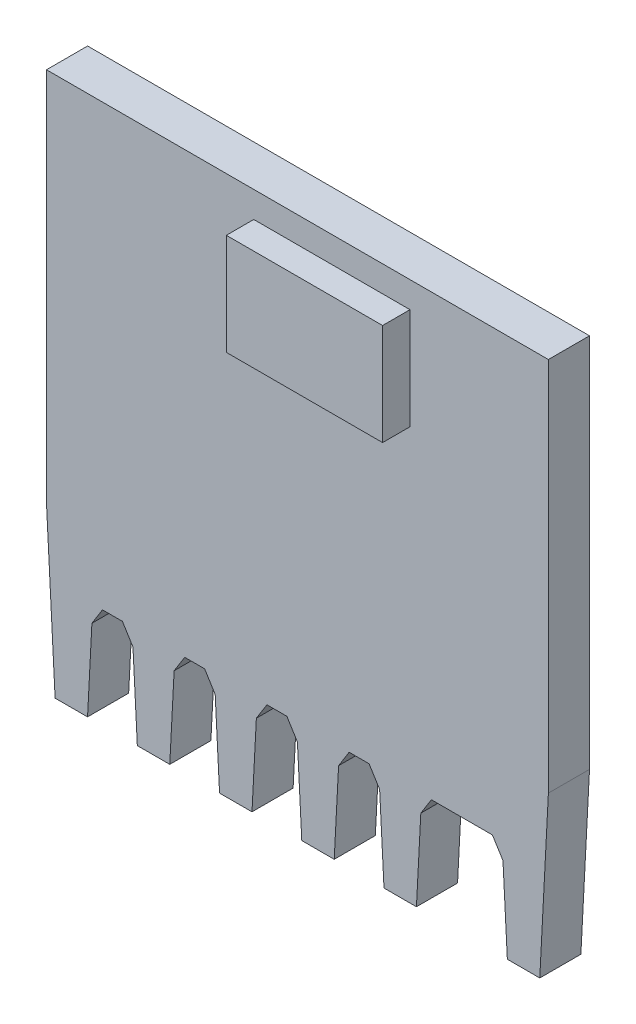
SolidWorks part; units mm, degrees
ref_plane "Front Plane" through (0, 0, 0) normal (0, 0, 1) x (1, 0, 0)
ref_plane "Top Plane" through (0, 0, 0) normal (0, 1, 0) x (1, 0, 0)
ref_plane "Right Plane" through (0, 0, 0) normal (1, 0, 0) x (0, 0, -1)
sketch "Sketch1" plane through (0, 0, 0) normal (0, 0, 1) x (1, 0, 0)
  line L0 (0, 0) -> (0, 19.7) construction
  line L1 (0, 19.7) -> (18.3124, 19.7) construction
  line L2 (18.3124, 19.7) -> (18.3124, 0) construction
  line L3 (18.3124, 0) -> (0, 0) construction
  line L4 (0, 3) -> (18.3124, 3) construction
  line L5 (0, 6) -> (18.3124, 6) construction
  line L6 (0.9062, 6) -> (0.9062, 0) construction
  line L7 (3.9062, 6) -> (3.9062, 0) construction
  line L8 (6.9062, 6) -> (6.9062, 0) construction
  line L9 (9.9062, 6) -> (9.9062, 0) construction
  line L10 (12.9062, 6) -> (12.9062, 0) construction
  line L11 (17.4062, 6) -> (17.4062, 0) construction
  line L12 (0.9062, 3) -> (3.9062, 3) construction
  line L13 (3.9062, 3) -> (6.9062, 3) construction
  line L14 (6.9062, 3) -> (9.9062, 3) construction
  line L15 (9.9062, 3) -> (12.9062, 3) construction
  line L16 (12.9062, 3) -> (17.4062, 3) construction
  line L17 (0.9062, 3) -> (0, 3) construction
  line L18 (17.4062, 3) -> (18.3124, 3) construction
  line L19 (2.4062, 3) -> (2.4062, 0) construction
  line L20 (5.4062, 3) -> (5.4062, 0) construction
  line L21 (8.4062, 3) -> (8.4062, 0) construction
  line L22 (11.4062, 3) -> (11.4062, 0) construction
  line L23 (15.1562, 3) -> (15.1562, 0) construction
  line L24 (14.4062, 3.75) -> (15.9062, 3.75) construction
  line L25 (0, 6) -> (0.3144, 0)
  line L26 (0.3144, 0) -> (1.4979, 0)
  line L27 (1.4979, 0) -> (1.6572, 3.0393)
  line L28 (3.1552, 3.0393) -> (3.3144, 0)
  line L29 (3.3144, 0) -> (4.4979, 0)
  line L30 (4.4979, 0) -> (4.6572, 3.0393)
  line L31 (6.1552, 3.0393) -> (6.3144, 0)
  line L32 (6.3144, 0) -> (7.4979, 0)
  line L33 (7.4979, 0) -> (7.6572, 3.0393)
  line L34 (9.1552, 3.0393) -> (9.3144, 0)
  line L35 (9.3144, 0) -> (10.4979, 0)
  line L36 (10.4979, 0) -> (10.6572, 3.0393)
  line L37 (12.1552, 3.0393) -> (12.3144, 0)
  line L38 (12.3144, 0) -> (13.4979, 0)
  line L39 (13.4979, 0) -> (13.6572, 3.0393)
  line L40 (16.6552, 3.0393) -> (16.8144, 0)
  line L41 (16.8144, 0) -> (17.9979, 0)
  line L42 (17.9979, 0) -> (18.3124, 6)
  line L44 (1.6572, 3.0393) -> (2.0426, 3.656)
  line L45 (0, 6) -> (0, 19.7)
  line L46 (0, 19.7) -> (18.3124, 19.7)
  line L47 (18.3124, 19.7) -> (18.3124, 6)
  line L48 (9.1562, 19.7) -> (9.1562, 6) construction
  line L49 (2.0426, 3.656) -> (2.7698, 3.656)
  line L50 (2.7698, 3.656) -> (3.1552, 3.0393)
  line L51 (4.6572, 3.0393) -> (5.0426, 3.656)
  line L52 (5.0426, 3.656) -> (5.7698, 3.656)
  line L53 (5.7698, 3.656) -> (6.1552, 3.0393)
  line L54 (7.6572, 3.0393) -> (8.0426, 3.656)
  line L55 (8.0426, 3.656) -> (8.7698, 3.656)
  line L56 (8.7698, 3.656) -> (9.1552, 3.0393)
  line L57 (10.6572, 3.0393) -> (11.0426, 3.656)
  line L58 (11.0426, 3.656) -> (11.7698, 3.656)
  line L59 (11.7698, 3.656) -> (12.1552, 3.0393)
  line L60 (13.6572, 3.0393) -> (14.0426, 3.656)
  line L61 (14.0426, 3.656) -> (16.2698, 3.656)
  line L62 (16.2698, 3.656) -> (16.6552, 3.0393)
  arc A0 (3.1552, 3.0393) -> (1.6572, 3.0393) centre (2.4062, 3) ccw construction
  arc A1 (6.1552, 3.0393) -> (4.6572, 3.0393) centre (5.4062, 3) ccw construction
  arc A2 (9.1552, 3.0393) -> (7.6572, 3.0393) centre (8.4062, 3) ccw construction
  arc A3 (12.1552, 3.0393) -> (10.6572, 3.0393) centre (11.4062, 3) ccw construction
  arc A4 (13.6572, 3.0393) -> (14.4062, 3.75) centre (14.4062, 3) cw construction
  arc A5 (16.6552, 3.0393) -> (15.9062, 3.75) centre (15.9062, 3) ccw construction
  dimension "D7" = 0.75
  dimension "D1" = 3
  dimension "D2" = 6
  dimension "D3" = 13.7
  dimension "D4" = 3
  dimension "D6" = 4.5
  dimension "D8" = 3
  dimension "D9" = 18.3124
  dimension "D10" = 19.7
extrude "Boss-Extrude1" add sketch "Sketch1" along normal blind 1.5
sketch "Sketch3" plane through (0, 0, 0) normal (0, 0, 1) x (1, 0, 0)
  line L0 (-0.4005, 6) -> (18.7129, 6)
  line L1 (18.7129, 3) -> (-0.4005, 3) construction
  line L2 (-0.4005, 0) -> (18.7129, 0) construction
  line L3 (-0.4005, -0.5) -> (18.7129, -0.5) construction
  line L4 (18.7129, -0.5) -> (18.7129, 6) construction
  line L5 (-0.4005, 6) -> (-0.4005, -0.5) construction
  line L6 (18.3124, 0) -> (0, 0) construction
  line L7 (0, 3) -> (18.3124, 3) construction
  line L8 (0, 6) -> (18.3124, 6) construction
  line L9 (0.3407, -0.5) -> (0, 6) construction
  line L10 (18.3124, 6) -> (17.9717, -0.5) construction
  line L11 (17.9979, 0) -> (18.3124, 6) construction
  line L12 (0, 6) -> (0.3144, 0) construction
  line L13 (5.4062, 6) -> (5.4062, -0.5) construction
  line L14 (3.9062, 6) -> (3.9062, -0.5) construction
  line L15 (5.4062, 3) -> (5.4062, 0) construction
  line L16 (3.1572, 3) -> (3.3407, -0.5) construction
  line L17 (2.7567, 3) -> (2.9401, -0.5)
  line L18 (3.1552, 3.0393) -> (3.3144, 0) construction
  line L19 (2.9401, -0.5) -> (4.8723, -0.5)
  line L20 (4.8723, -0.5) -> (5.0557, 3)
  line L21 (2.8484, 1.25) -> (3.2478, 1.2709) construction
  line L22 (5.9401, -0.5) -> (5.7567, 3)
  line L26 (7.8723, -0.5) -> (5.9401, -0.5)
  line L27 (8.0557, 3) -> (7.8723, -0.5)
  line L30 (2.4062, -0.5) -> (2.4062, 6) construction
  line L31 (2.4062, 3) -> (2.4062, 0) construction
  line L32 (8.4062, 6) -> (8.4062, -0.5) construction
  line L34 (11.4062, -0.5) -> (11.4062, 6) construction
  line L35 (15.1562, -0.5) -> (15.1562, 6) construction
  line L36 (8.4062, 3) -> (8.4062, 0) construction
  line L37 (11.4062, 3) -> (11.4062, 0) construction
  line L38 (15.1562, 3) -> (15.1562, 0) construction
  line L39 (10.8723, -0.5) -> (11.0557, 3)
  line L40 (8.9401, -0.5) -> (10.8723, -0.5)
  line L41 (8.7567, 3) -> (8.9401, -0.5)
  line L42 (11.9401, -0.5) -> (11.7567, 3)
  line L43 (13.8723, -0.5) -> (11.9401, -0.5)
  line L44 (14.0557, 3) -> (13.8723, -0.5)
  line L45 (16.4401, -0.5) -> (18.3723, -0.5)
  line L46 (16.2567, 3) -> (16.4401, -0.5)
  line L47 (18.3723, -0.5) -> (18.7129, 6)
  line L48 (1.8723, -0.5) -> (-0.0599, -0.5)
  line L49 (2.0557, 3) -> (1.8723, -0.5)
  line L50 (-0.0599, -0.5) -> (-0.4005, 6)
  line L51 (16.2567, 3) -> (14.0557, 3)
  line L52 (11.7567, 3) -> (11.0557, 3)
  line L53 (8.7567, 3) -> (8.0557, 3)
  line L54 (5.7567, 3) -> (5.0557, 3)
  line L55 (2.7567, 3) -> (2.0557, 3)
  dimension "D1" = 0.5
  dimension "D2" = 0.4
ref_plane "Plane1" through (3.9062, 0, 0) normal (1, 0, 0) x (0, 0, -1)
sketch "Sketch4" plane through (3.9062, 0, 0) normal (1, 0, 0) x (0, 0, -1)
  line L0 (0, 6) -> (0, -0.5) construction
  line L1 (0.6, 6) -> (-2.1, 6) construction
  line L2 (0.6, 6) -> (0.6, -0.5) construction
  line L3 (0.6, -0.5) -> (-2.1, -0.5) construction
  line L4 (-2.1, 6) -> (-2.1, -0.5) construction
  line L5 (-0.75, -0.5) -> (-0.75, 6) construction
  line L6 (-1.5, 6) -> (-1.5, -0.5) construction
  line L7 (0.6, 2.4005) -> (-2.1, 2.4005) construction
  line L8 (0.3, 6) -> (0.3, -0.5) construction
  line L9 (0.6, 2.4005) -> (3.846, 6) construction
  line L10 (2.2302, 6) -> (0.6, 4.1923) construction
  line L11 (0.6, 4.1923) -> (1.7139, 3.1878) construction
  line L12 (1.7139, 3.1878) -> (4.25, 6)
  line L13 (4.25, 6) -> (0.6, 6) construction
  line L14 (0.3, 1) -> (-1.8, 1) construction
  line L15 (-2.1, 0) -> (0.6, 0) construction
  line L16 (1.7139, 3.1878) -> (1.4912, 3.3887)
  line L17 (1.4912, 3.3887) -> (0.6, 2.4005)
  line L18 (-3.2139, 3.1878) -> (-5.75, 6)
  line L19 (-3.2139, 3.1878) -> (-2.9912, 3.3887)
  line L20 (-2.9912, 3.3887) -> (-2.1, 2.4005)
  line L21 (-2.1, 6) -> (-5.75, 6) construction
  line L22 (0.6, 3.0724) -> (3.2401, 6) construction
  arc A0 (0.4965, 2.2224) -> (0.6, -0.5) centre (4.2, 1) ccw
  arc A1 (0.6, 2.4005) -> (0.4965, 2.2224) centre (0.9713, 2.0656) ccw
  arc A2 (-2.1, 2.4005) -> (-1.9965, 2.2224) centre (-2.4713, 2.0656) cw
  arc A3 (-1.9965, 2.2224) -> (-2.1, -0.5) centre (-5.7, 1) cw
  dimension "D6" = 0.5
  dimension "D1" = 0.6
  dimension "D2" = 0.3
  dimension "D3" = 1.5
  dimension "D4" = 1
  dimension "D5" = 0.3
  dimension "D7" = 10
sketch "Sketch5" plane through (0, 0, 0) normal (1, 0, 0) x (0, 0, -1)
  line L0 (2.2302, 6) -> (0.6, 4.1923) construction
  line L1 (0.6, 4.1923) -> (1.7139, 3.1878) construction
  line L2 (1.7139, 3.1878) -> (4.25, 6) construction
  line L3 (2.2302, 6) -> (0.6, 4.1923) construction
  line L4 (0.6, 4.1923) -> (1.7139, 3.1878) construction
  line L5 (1.7139, 3.1878) -> (4.25, 6) construction
ref_plane "Plane2" through (0, 2.6105, -2.3541) normal (0, 0.7426, -0.6697) x (1, 0, 0)
sketch "Sketch6" plane through (0, 2.6105, -2.3541) normal (0, 0.7426, -0.6697) x (1, 0, 0)
  line L1 (3.9062, -2.362) -> (3.9062, -0.862) construction
  line L2 (3.9062, -2.362) -> (3.9062, -5.0612) construction
  line L3 (4.6562, -5.0612) -> (3.1562, -5.0612)
  line L4 (4.6562, -1.612) -> (3.1562, -1.612) construction
  line L5 (3.1562, -1.612) -> (3.1562, -5.0612)
  line L6 (4.6562, -1.612) -> (4.6562, -5.0612)
  line L10 (2.4062, -5.0612) -> (15.1562, -5.0612) construction
  line L11 (15.1562, -5.0612) -> (15.1562, -0.862) construction
  line L12 (15.1562, -0.862) -> (2.4062, -0.862) construction
  line L13 (2.4062, -0.862) -> (2.4062, -5.0612) construction
  line L14 (15.1562, 0.3349) -> (15.1562, -4.0182) construction
  line L15 (2.4062, 0.3349) -> (2.4062, -4.0182) construction
  line L16 (11.4062, -5.0612) -> (11.4062, -0.862) construction
  line L17 (8.4062, -5.0612) -> (8.4062, -0.862) construction
  line L18 (5.4062, -5.0612) -> (5.4062, -0.862) construction
  line L19 (5.4062, -4.0182) -> (5.4062, 0.3349) construction
  line L20 (8.4062, -4.0182) -> (8.4062, 0.3349) construction
  line L21 (11.4062, 0.3349) -> (11.4062, -4.0182) construction
  line L22 (0.1562, -1.612) -> (0.1562, -5.0612)
  line L23 (0.1562, -5.0612) -> (1.6562, -5.0612)
  line L24 (1.6562, -1.612) -> (1.6562, -5.0612)
  line L25 (7.6562, -1.612) -> (7.6562, -5.0612)
  line L26 (6.1562, -5.0612) -> (7.6562, -5.0612)
  line L27 (6.1562, -1.612) -> (6.1562, -5.0612)
  line L28 (10.6562, -1.612) -> (10.6562, -5.0612)
  line L29 (10.6562, -5.0612) -> (9.1562, -5.0612)
  line L30 (9.1562, -1.612) -> (9.1562, -5.0612)
  line L31 (13.6562, -1.612) -> (13.6562, -5.0612)
  line L32 (12.1562, -5.0612) -> (13.6562, -5.0612)
  line L33 (12.1562, -1.612) -> (12.1562, -5.0612)
  line L34 (18.1562, -1.612) -> (18.1562, -5.0612)
  line L35 (18.1562, -5.0612) -> (16.6562, -5.0612)
  line L36 (16.6562, -1.612) -> (16.6562, -5.0612)
  circle A0 centre (3.9062, -1.612) radius 0.75 construction
  arc A1 (4.6562, -1.612) -> (3.1562, -1.612) centre (3.9062, -1.612) ccw
  arc A2 (0.1562, -1.612) -> (1.6562, -1.612) centre (0.9062, -1.612) cw
  arc A3 (6.1562, -1.612) -> (7.6562, -1.612) centre (6.9062, -1.612) cw
  arc A4 (10.6562, -1.612) -> (9.1562, -1.612) centre (9.9062, -1.612) ccw
  arc A5 (12.1562, -1.612) -> (13.6562, -1.612) centre (12.9062, -1.612) cw
  arc A6 (18.1562, -1.612) -> (16.6562, -1.612) centre (17.4062, -1.612) ccw
ref_plane "Plane3" through (0, 1.6223, -1.463) normal (0, 0.7426, -0.6697) x (1, 0, 0)
sketch "Sketch7" plane through (0, 1.6223, -1.463) normal (0, 0.7426, -0.6697) x (1, 0, 0)
  line L0 (3.1562, -1.612) -> (3.1562, -5.0612) construction
  line L1 (4.6562, -5.0612) -> (3.1562, -5.0612) construction
  line L2 (4.6562, -1.612) -> (4.6562, -5.0612) construction
  line L3 (3.1562, -1.612) -> (3.1562, -5.0612) construction
  line L4 (4.6562, -5.0612) -> (3.1562, -5.0612) construction
  line L5 (4.6562, -1.612) -> (4.6562, -5.0612) construction
  line L6 (3.9062, -0.862) -> (3.9062, -5.0612) construction
  line L7 (4.6562, -1.612) -> (3.1562, -1.612) construction
  line L8 (4.6562, -2.362) -> (3.1562, -2.362) construction
  line L9 (3.4562, -1.612) -> (3.4562, -2.362)
  line L10 (3.4562, -2.362) -> (4.3562, -2.362)
  line L11 (4.3562, -2.362) -> (4.3562, -1.612)
  line L12 (2.4062, -0.862) -> (2.4062, -5.0612) construction
  line L13 (2.4062, -5.0612) -> (15.1562, -5.0612) construction
  line L14 (15.1562, -0.862) -> (2.4062, -0.862) construction
  line L15 (5.4062, -5.0612) -> (5.4062, -0.862) construction
  line L16 (8.4062, -5.0612) -> (8.4062, -0.862) construction
  line L17 (11.4062, -5.0612) -> (11.4062, -0.862) construction
  line L18 (15.1562, -5.0612) -> (15.1562, -0.862) construction
  line L19 (2.4062, -0.862) -> (2.4062, -5.0612) construction
  line L20 (2.4062, -5.0612) -> (15.1562, -5.0612) construction
  line L21 (15.1562, -0.862) -> (2.4062, -0.862) construction
  line L22 (5.4062, -5.0612) -> (5.4062, -0.862) construction
  line L23 (8.4062, -5.0612) -> (8.4062, -0.862) construction
  line L24 (11.4062, -5.0612) -> (11.4062, -0.862) construction
  line L25 (15.1562, -5.0612) -> (15.1562, -0.862) construction
  line L26 (0.4562, -2.362) -> (0.4562, -1.612)
  line L27 (1.3562, -2.362) -> (0.4562, -2.362)
  line L28 (1.3562, -1.612) -> (1.3562, -2.362)
  line L29 (7.3562, -2.362) -> (6.4562, -2.362)
  line L30 (7.3562, -1.612) -> (7.3562, -2.362)
  line L31 (6.4562, -2.362) -> (6.4562, -1.612)
  line L32 (9.4562, -1.612) -> (9.4562, -2.362)
  line L33 (10.3562, -2.362) -> (10.3562, -1.612)
  line L34 (9.4562, -2.362) -> (10.3562, -2.362)
  line L35 (13.3562, -1.612) -> (13.3562, -2.362)
  line L36 (12.4562, -2.362) -> (12.4562, -1.612)
  line L37 (13.3562, -2.362) -> (12.4562, -2.362)
  line L38 (16.9562, -1.612) -> (16.9562, -2.362)
  line L39 (17.8562, -2.362) -> (17.8562, -1.612)
  line L40 (16.9562, -2.362) -> (17.8562, -2.362)
  arc A0 (4.6562, -1.612) -> (3.1562, -1.612) centre (3.9062, -1.612) ccw construction
  arc A1 (4.6562, -1.612) -> (3.1562, -1.612) centre (3.9062, -1.612) ccw construction
  circle A2 centre (3.9062, -1.612) radius 0.45 construction
  arc A3 (4.3562, -1.612) -> (3.4562, -1.612) centre (3.9062, -1.612) ccw
  arc A4 (0.4562, -1.612) -> (1.3562, -1.612) centre (0.9062, -1.612) cw
  arc A5 (6.4562, -1.612) -> (7.3562, -1.612) centre (6.9062, -1.612) cw
  arc A6 (10.3562, -1.612) -> (9.4562, -1.612) centre (9.9062, -1.612) ccw
  arc A7 (12.4562, -1.612) -> (13.3562, -1.612) centre (12.9062, -1.612) cw
  arc A8 (17.8562, -1.612) -> (16.9562, -1.612) centre (17.4062, -1.612) ccw
ref_plane "bisect" through (0, 0, 0.75) normal (0, 0, 1) x (1, 0, 0)
ref_plane "insert_surface" through (0, 6, 0) normal (0, 1, 0) x (1, 0, 0)
sketch "Sketch8" plane through (0, 6, 0) normal (0, 1, 0) x (1, 0, 0)
  line L0 (18.7129, -0.75) -> (-0.4005, -0.75) construction
  line L1 (-0.4005, 0.6) -> (18.7129, 0.6)
  line L2 (-0.4005, 0.6) -> (-0.4005, -2.1)
  line L3 (-0.4005, -2.1) -> (18.7129, -2.1)
  line L4 (18.7129, 0.6) -> (18.7129, -2.1)
  line L5 (9.1562, 0.6) -> (9.1562, -2.1) construction
  line L6 (0, 0) -> (18.3124, 0) construction
  line L7 (0, 0) -> (0, -1.5) construction
  line L8 (0, -1.5) -> (18.3124, -1.5) construction
  line L9 (18.3124, 0) -> (18.3124, -1.5) construction
  line L10 (18.7129, 0.3) -> (-0.4005, 0.3) construction
  line L11 (18.7129, -1.8) -> (-0.4005, -1.8) construction
sketch "Sketch9" plane through (0, 0, 0) normal (0, 0, 1) x (1, 0, 0)
  line L0 (18.3723, -0.5) -> (18.7129, 6) construction
  line L1 (-0.4005, 6) -> (18.7129, 6) construction
  line L2 (-0.0599, -0.5) -> (-0.4005, 6) construction
  line L3 (1.8723, -0.5) -> (-0.0599, -0.5) construction
  line L4 (2.0557, 3) -> (1.8723, -0.5) construction
  line L5 (2.7567, 3) -> (2.0557, 3) construction
  line L6 (2.7567, 3) -> (2.9401, -0.5) construction
  line L7 (2.9401, -0.5) -> (4.8723, -0.5) construction
  line L8 (4.8723, -0.5) -> (5.0557, 3) construction
  line L9 (5.7567, 3) -> (5.0557, 3) construction
  line L10 (5.9401, -0.5) -> (5.7567, 3) construction
  line L11 (7.8723, -0.5) -> (5.9401, -0.5) construction
  line L12 (8.0557, 3) -> (7.8723, -0.5) construction
  line L13 (8.7567, 3) -> (8.0557, 3) construction
  line L14 (8.7567, 3) -> (8.9401, -0.5) construction
  line L15 (8.9401, -0.5) -> (10.8723, -0.5) construction
  line L16 (10.8723, -0.5) -> (11.0557, 3) construction
  line L17 (11.7567, 3) -> (11.0557, 3) construction
  line L18 (11.9401, -0.5) -> (11.7567, 3) construction
  line L19 (13.8723, -0.5) -> (11.9401, -0.5) construction
  line L20 (14.0557, 3) -> (13.8723, -0.5) construction
  line L21 (16.2567, 3) -> (14.0557, 3) construction
  line L22 (16.2567, 3) -> (16.4401, -0.5) construction
  line L23 (16.4401, -0.5) -> (18.3723, -0.5) construction
  line L24 (18.3723, -0.5) -> (18.7129, 6)
  line L25 (-0.4005, 6) -> (18.7129, 6) construction
  line L26 (-0.0599, -0.5) -> (-0.4005, 6)
  line L27 (1.8723, -0.5) -> (-0.0599, -0.5)
  line L28 (2.0557, 3) -> (1.8723, -0.5)
  line L29 (2.7567, 3) -> (2.0557, 3) construction
  line L30 (2.7567, 3) -> (2.9401, -0.5)
  line L31 (2.9401, -0.5) -> (4.8723, -0.5)
  line L32 (4.8723, -0.5) -> (5.0557, 3)
  line L33 (5.7567, 3) -> (5.0557, 3) construction
  line L34 (5.9401, -0.5) -> (5.7567, 3)
  line L35 (7.8723, -0.5) -> (5.9401, -0.5)
  line L36 (8.0557, 3) -> (7.8723, -0.5)
  line L37 (8.7567, 3) -> (8.0557, 3) construction
  line L38 (8.7567, 3) -> (8.9401, -0.5)
  line L39 (8.9401, -0.5) -> (10.8723, -0.5)
  line L40 (10.8723, -0.5) -> (11.0557, 3)
  line L41 (11.7567, 3) -> (11.0557, 3) construction
  line L42 (11.9401, -0.5) -> (11.7567, 3)
  line L43 (13.8723, -0.5) -> (11.9401, -0.5)
  line L44 (14.0557, 3) -> (13.8723, -0.5)
  line L45 (16.2567, 3) -> (14.0557, 3) construction
  line L46 (16.2567, 3) -> (16.4401, -0.5)
  line L47 (16.4401, -0.5) -> (18.3723, -0.5)
  line L48 (16.2567, 3) -> (16.2567, 6)
  line L49 (14.0557, 3) -> (14.0557, 6)
  line L50 (11.7567, 3) -> (11.7567, 6)
  line L51 (18.7129, 6) -> (-0.4005, 6) construction
  line L52 (11.0557, 3) -> (11.0557, 6)
  line L53 (-0.4005, 6) -> (18.7129, 6) construction
  line L54 (8.7567, 3) -> (8.7567, 6)
  line L55 (8.0557, 3) -> (8.0557, 6)
  line L58 (5.7567, 3) -> (5.7567, 6)
  line L60 (5.0557, 3) -> (5.0557, 6)
  line L62 (15.1562, -0.5) -> (15.1562, 6) construction
  line L63 (15.1562, -0.5) -> (15.1562, 6) construction
  line L64 (2.7567, 3) -> (2.7567, 6)
  line L65 (2.0557, 3) -> (2.0557, 6)
  line L67 (18.7129, 6) -> (16.2567, 6)
  line L68 (14.0557, 6) -> (11.7567, 6)
  line L69 (11.0557, 6) -> (8.7567, 6)
  line L70 (8.0557, 6) -> (5.7567, 6)
  line L71 (5.0557, 6) -> (2.7567, 6)
  line L72 (2.0557, 6) -> (-0.4005, 6)
sketch "rgb_led" plane through (0, 0, 1.5) normal (0, 0, 1) x (1, 0, 0)
  line L0 (13.2624, 16.9) -> (7.5624, 16.9) construction
  line L1 (0, 6) -> (18.3124, 6) construction
  line L2 (10.4124, 16.9) -> (10.4124, 15.05) construction
  line L3 (10.4124, 19.7) -> (10.4124, 16.9) construction
  line L4 (18.3124, 19.7) -> (18.3124, 6) construction
  line L5 (0, 6) -> (0, 19.7) construction
  line L6 (13.2624, 18.75) -> (7.5624, 18.75)
  line L7 (13.2624, 18.75) -> (13.2624, 15.05)
  line L8 (13.2624, 15.05) -> (7.5624, 15.05)
  line L9 (7.5624, 18.75) -> (7.5624, 15.05)
  line L10 (0, 19.7) -> (18.3124, 19.7) construction
  line L11 (0, 19.7) -> (18.3124, 19.7) construction
  line L16 (0, 6) -> (18.3124, 6) construction
  line L17 (18.3124, 6) -> (18.3124, 19.7) construction
  line L18 (0, 19.7) -> (0, 6) construction
  dimension "D1" = 2.8
  dimension "D2" = 3.7
  dimension "D3" = 5.7
  dimension "D4" = 7.9
extrude "Boss-Extrude2" add sketch "rgb_led" along normal blind 1
